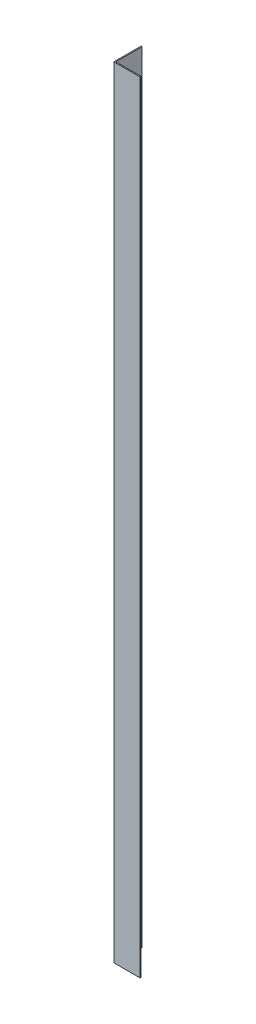
SolidWorks part; units mm, degrees
ref_plane "Front Plane" through (0, 0, 0) normal (0, 0, 1) x (1, 0, 0)
ref_plane "Top Plane" through (0, 0, 0) normal (0, 1, 0) x (1, 0, 0)
ref_plane "Right Plane" through (0, 0, 0) normal (1, 0, 0) x (0, 0, -1)
sketch "Sketch1" plane through (0, 0, 0) normal (0, 1, 0) x (1, 0, 0)
  line L0 (12.5, -12.5) -> (12.5, -13.5)
  line L1 (12.5, -12.5) -> (-11.5, -12.5)
  line L2 (12.5, 11.5) -> (12.5, 12.5)
  line L4 (-12.5, -12.5) -> (-12.5, 12.5)
  line L5 (12.5, -12.5) -> (-12.5, 12.5) construction
  line L6 (12.5, 12.5) -> (-11.5, -11.5) construction
  line L7 (11.5, 11.5) -> (12.5, 11.5)
  line L8 (-11.5, 11.5) -> (-11.5, -12.5)
  line L9 (-11.5, -13.5) -> (12.5, -13.5)
  line L11 (-11.5, 11.5) -> (12.5, -12.5) construction
  line L12 (-10.5, -12.5) -> (1, -1) construction
  line L13 (-11.5, 11.5) -> (-11.5, 12.5)
  line L16 (-11.5, -13.5) -> (-12.5, -13.5)
  line L17 (-12.5, -12.5) -> (-12.5, -13.5)
  line L18 (-12.5, 12.5) -> (-11.5, 12.5)
  point P0 (0, 0)
  point P6 (1, -1)
  dimension "D1" = 25
  dimension "D2" = 25
  dimension "D3" = 25
  dimension "D5" = 1
extrude "Boss-Extrude1" add sketch "Sketch1" along normal blind 740 contours L18 L4 L17 L16 L9 L0 L1 L8 L13
